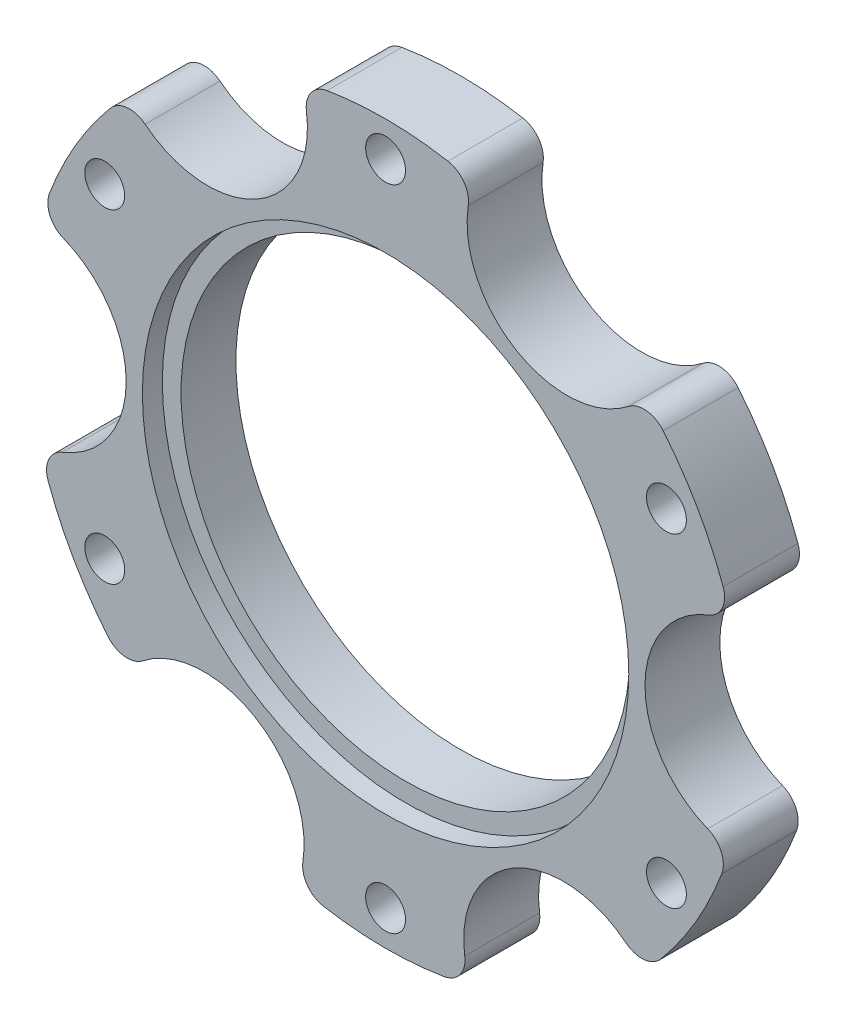
SolidWorks part; units mm, degrees
ref_plane "前视基准面" through (0, 0, 0) normal (0, 0, 1) x (1, 0, 0)
ref_plane "上视基准面" through (0, 0, 0) normal (0, 1, 0) x (1, 0, 0)
ref_plane "右视基准面" through (0, 0, 0) normal (1, 0, 0) x (0, 0, -1)
other "Configuration Table"
sketch "草图1" plane through (0, 0, 0) normal (0, 0, 1) x (1, 0, 0)
  circle A0 centre (0, 0) radius 9
  circle A1 centre (0, 0) radius 14.4
  dimension "D1" = 18
  dimension "D2" = 28.8
extrude "凸台-拉伸1" add sketch "草图1" along normal blind 3
sketch "草图2" plane through (0, 0, 3) normal (0, 0, 1) x (1, 0, 0)
  circle A0 centre (0, 0) radius 9.75
  dimension "D1" = 19.5
extrude "切除-拉伸1" cut sketch "草图2" against normal blind 0.8
sketch "草图3" plane through (0, 0, 3) normal (0, 0, 1) x (1, 0, 0)
  circle A0 centre (0, 0) radius 13 construction
  circle A1 centre (0, 13) radius 0.8
  circle A2 centre (11.2583, 6.5) radius 0.8
  circle A3 centre (11.2583, -6.5) radius 0.8
  circle A4 centre (0, -13) radius 0.8
  circle A5 centre (-11.2583, -6.5) radius 0.8
  circle A6 centre (-11.2583, 6.5) radius 0.8
  point P17 (0, 0)
  dimension "D1" = 26
  dimension "D2" = 1.6
  dimension "D3" = 6
extrude "切除-拉伸2" cut sketch "草图3" against normal blind 10
sketch "草图4" plane through (0, 0, 3) normal (0, 0, 1) x (1, 0, 0)
  line L0 (0, 0) -> (0, 50000) construction
  line L1 (0, -0.155) -> (25000, 43301.1152) construction
  circle A0 centre (7.267, 12.4318) radius 4
  circle A1 centre (0, 0) radius 14.4 construction
  circle A2 centre (14.3998, -0.0775) radius 4
  circle A3 centre (7.1328, -12.5093) radius 4
  circle A4 centre (-7.267, -12.4318) radius 4
  circle A5 centre (-14.3998, 0.0775) radius 4
  circle A6 centre (-7.1328, 12.5093) radius 4
  point P21 (0, 0)
  dimension "D2" = 8
  dimension "D1" = 30
  dimension "D3" = 6
extrude "切除-拉伸3" cut sketch "草图4" against normal blind 10
fillet "圆角1" radius 1 12 edges at (-10.2987, 10.0646, 1.5) (-3.4165, 13.9888, 1.5) (-13.8656, -3.8867, 1.5) (-13.8229, 4.0357, 1.5) (-3.5668, -13.9513, 1.5) (-10.4065, -9.9532, 1.5) (10.2987, -10.0646, 1.5) (3.4165, -13.9888, 1.5) (13.8656, 3.8867, 1.5) (13.8229, -4.0357, 1.5) (3.5668, 13.9513, 1.5) (10.4065, 9.9532, 1.5)
